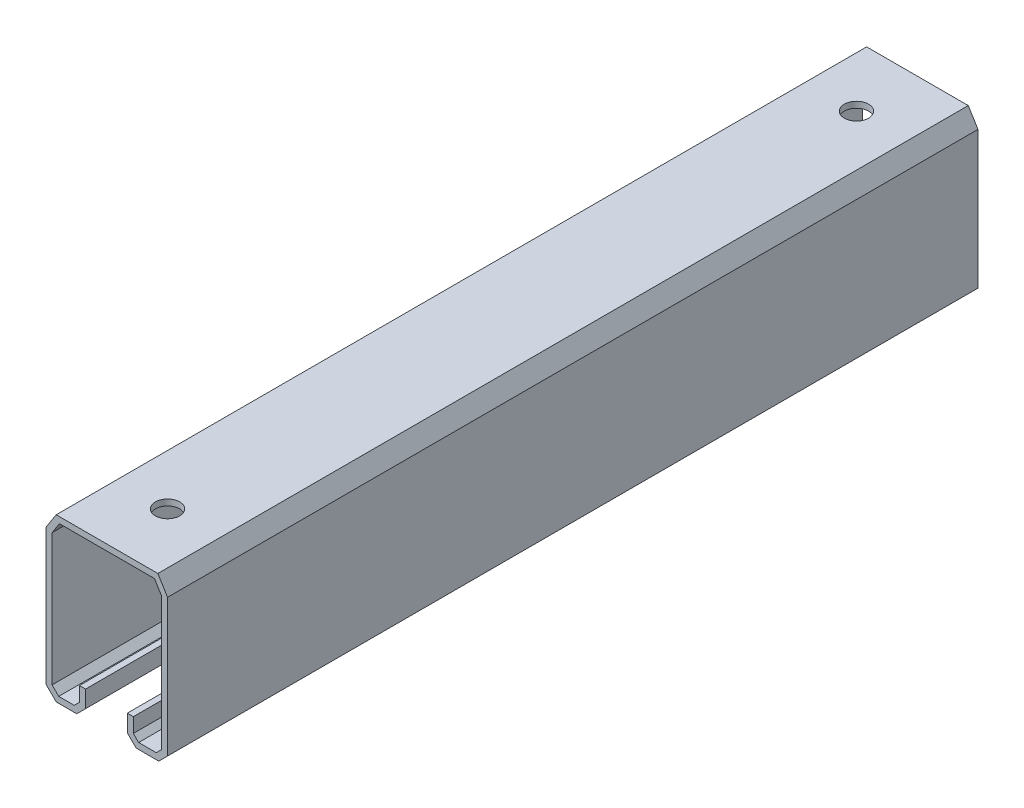
SolidWorks part; units mm, degrees
ref_plane "Alzado" through (0, 0, 0) normal (0, 0, 1) x (1, 0, 0)
ref_plane "Planta" through (0, 0, 0) normal (0, 1, 0) x (1, 0, 0)
ref_plane "Vista lateral" through (0, 0, 0) normal (1, 0, 0) x (0, 0, -1)
sketch "Croquis1" plane through (0, 0, 0) normal (0, 0, 1) x (1, 0, 0)
  line L0 (-10.4697, -27.2402) -> (-10.4697, -35.6509)
  line L1 (-30, -40) -> (30, -40) construction
  line L2 (-30, -40) -> (-30, 40) construction
  line L3 (-30, 40) -> (30, 40) construction
  line L4 (30, -40) -> (30, 40) construction
  line L5 (-30, -40) -> (30, 40) construction
  line L6 (-30, 40) -> (30, -40) construction
  line L7 (-10.4697, -35.6509) -> (-14.8188, -40)
  line L8 (-14.8188, -40) -> (-24.9711, -40)
  line L9 (-24.9711, -40) -> (-30, -34.9711)
  line L10 (-30, -34.9711) -> (-30, 32.2152)
  line L11 (-30, 32.2152) -> (-24.9711, 40)
  line L12 (-24.9711, 40) -> (25.2035, 40)
  line L13 (25.2035, 40) -> (30, 32.2152)
  line L14 (30, 32.2152) -> (30, -35.6509)
  line L15 (30, -35.6509) -> (25.6509, -40)
  line L16 (25.6509, -40) -> (14.4725, -40)
  line L17 (14.4725, -40) -> (10.1234, -35.6509)
  line L18 (10.1234, -35.6509) -> (10.1234, -27.2402)
  line L19 (-13.4697, -27.2402) -> (-13.4697, -34.4083)
  line L20 (-13.4697, -34.4083) -> (-16.0615, -37)
  line L21 (-16.0615, -37) -> (-23.7284, -37)
  line L22 (-23.7284, -37) -> (-27, -33.7284)
  line L23 (-27, -33.7284) -> (-27, 31.3305)
  line L24 (-27, 31.3305) -> (-23.3375, 37)
  line L25 (-23.3375, 37) -> (23.5282, 37)
  line L26 (23.5282, 37) -> (27, 31.3652)
  line L27 (27, 31.3652) -> (27, -34.4083)
  line L28 (27, -34.4083) -> (24.4083, -37)
  line L29 (24.4083, -37) -> (15.7151, -37)
  line L30 (15.7151, -37) -> (13.1234, -34.4083)
  line L31 (13.1234, -34.4083) -> (13.1234, -27.2402)
  line L32 (-13.4697, -27.2402) -> (-10.4697, -27.2402)
  line L33 (10.1234, -27.2402) -> (13.1234, -27.2402)
  point P0 (0, 0)
  dimension "D1" = 80
  dimension "D2" = 60
  dimension "D3" = 3
extrude "Saliente-Extruir1" add sketch "Croquis1" along normal mid plane 400
sketch "Croquis2" plane through (0, 40, 0) normal (0, 1, 0) x (1, 0, 0)
  circle A0 centre (0, 170) radius 6
  circle A1 centre (0, -170) radius 6
  dimension "D1" = 340
  dimension "D2" = 170
extrude "Cortar-Extruir1" cut sketch "Croquis2" against normal blind 400
equation "\"D2@Croquis2\"=\"D1@Croquis2\"/2"
